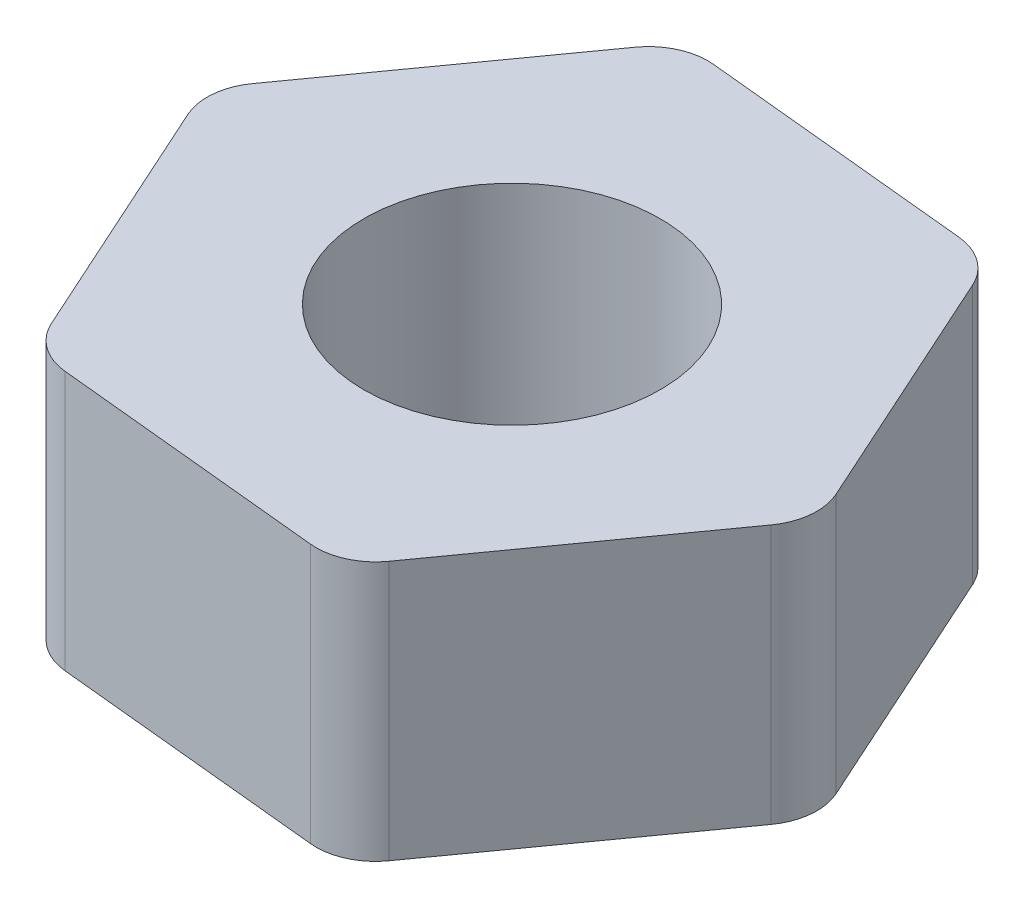
SolidWorks part; units mm, degrees
ref_plane "Front Plane" through (0, 0, 0) normal (0, 0, 1) x (1, 0, 0)
ref_plane "Top Plane" through (0, 0, 0) normal (0, 1, 0) x (1, 0, 0)
ref_plane "Right Plane" through (0, 0, 0) normal (1, 0, 0) x (0, 0, -1)
sketch "Sketch1" plane through (0, 0, 0) normal (0, 1, 0) x (1, 0, 0)
  line L1 (0.9523, -2.1039) -> (2.2982, -0.2272)
  line L2 (2.2982, -0.2272) -> (1.3459, 1.8767)
  line L3 (1.3459, 1.8767) -> (-0.9523, 2.1039)
  line L4 (-0.9523, 2.1039) -> (-2.2982, 0.2272)
  line L5 (-2.2982, 0.2272) -> (-1.3459, -1.8767)
  line L6 (-1.3459, -1.8767) -> (0.9523, -2.1039)
  circle A0 centre (0, 0) radius 2 construction
extrude "Boss-Extrude1" add sketch "Sketch1" along normal blind 1.75
fillet "Fillet1" radius 0.4 6 edges at (-2.2982, 0.875, -0.2272) (-0.9523, 0.875, -2.1039) (1.3459, 0.875, -1.8767) (2.2982, 0.875, 0.2272) (0.9523, 0.875, 2.1039) (-1.3459, 0.875, 1.8767)
sketch "Sketch7" plane through (0, 0, 0) normal (0, 1, 0) x (1, 0, 0)
  circle A0 centre (0, 0) radius 1
extrude "Cut-Extrude1" cut sketch "Sketch7" along normal through all
